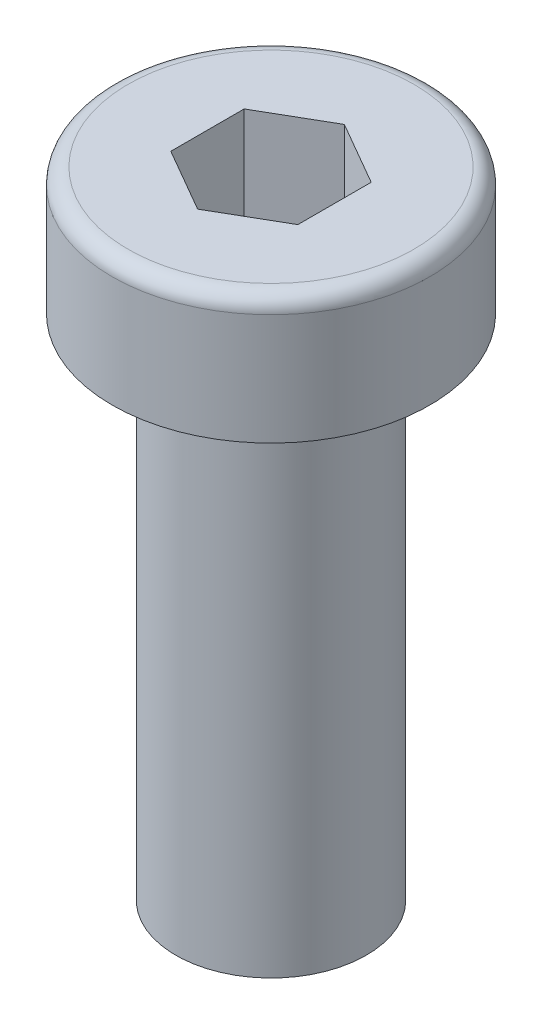
SolidWorks part; units mm, degrees
ref_plane "Front Plane" through (0, 0, 0) normal (0, 0, 1) x (1, 0, 0)
ref_plane "Top Plane" through (0, 0, 0) normal (0, 1, 0) x (1, 0, 0)
ref_plane "Right Plane" through (0, 0, 0) normal (1, 0, 0) x (0, 0, -1)
sketch "Sketch1" plane through (0, 0, 0) normal (0, 0, 1) x (1, 0, 0)
  line L0 (0, 20) -> (-4.5, 20)
  line L1 (-5, 19.5) -> (-5, 16)
  line L2 (-5, 16) -> (-3, 16)
  line L3 (-3, 16) -> (-3, 0)
  line L4 (-3, 0) -> (0, 0)
  line L5 (0, 0) -> (0, 20)
  arc A0 (-4.5, 20) -> (-5, 19.5) centre (-4.5, 19.5) ccw
  dimension "D5" = 0.5
  dimension "D1" = 4
  dimension "D2" = 5
  dimension "D3" = 16
  dimension "D4" = 3
revolve "Revolve1" add sketch "Sketch1" angle 360 about L5
sketch "Sketch2" plane through (0, 20, 0) normal (0, 1, 0) x (1, 0, 0)
  line L1 (0, 2.3094) -> (-2, 1.1547)
  line L2 (-2, 1.1547) -> (-2, -1.1547)
  line L3 (-2, -1.1547) -> (0, -2.3094)
  line L4 (0, -2.3094) -> (2, -1.1547)
  line L5 (2, -1.1547) -> (2, 1.1547)
  line L6 (2, 1.1547) -> (0, 2.3094)
  circle A0 centre (0, 0) radius 2.5
  circle A1 centre (0, 0) radius 2 construction
  dimension "D1" = 5
  dimension "D2" = 4
extrude "Cut-Extrude1" cut sketch "Sketch2" against normal blind 3 contours L1 L2 L3 L4 L5 L6
